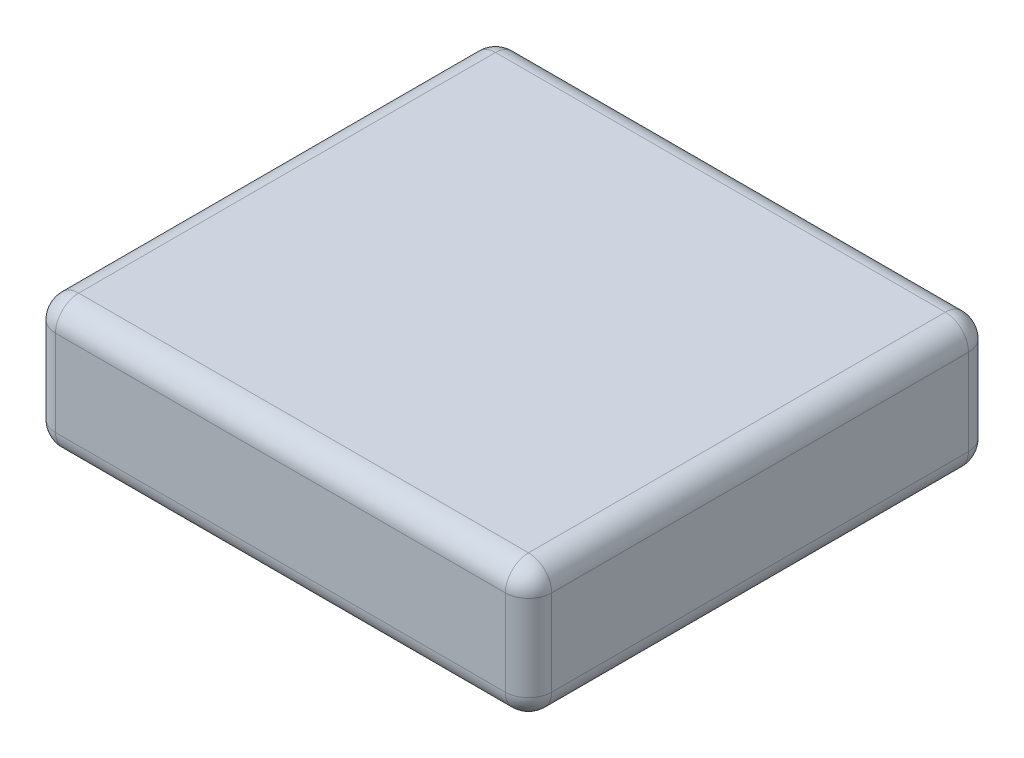
SolidWorks part; units mm, degrees
ref_plane "Front Plane" through (0, 0, 0) normal (0, 0, 1) x (1, 0, 0)
ref_plane "Top Plane" through (0, 0, 0) normal (0, 1, 0) x (1, 0, 0)
ref_plane "Right Plane" through (0, 0, 0) normal (1, 0, 0) x (0, 0, -1)
sketch "Sketch1" plane through (0, 0, 0) normal (0, 1, 0) x (1, 0, 0)
  line L1 (0, 0) -> (750, 0)
  line L2 (0, 0) -> (0, 700)
  line L3 (0, 700) -> (750, 700)
  line L4 (750, 0) -> (750, 700)
  dimension "D1" = 700
  dimension "D2" = 750
extrude "Boss-Extrude1" add sketch "Sketch1" along normal blind 200
fillet "Fillet1" radius 35 12 edges at (0, 100, 0) (750, 100, 0) (750, 100, -700) (0, 100, -700) (375, 200, -700) (750, 200, -350) (375, 200, 0) (0, 200, -350) (375, 0, 0) (750, 0, -350) (375, 0, -700) (0, 0, -350)
